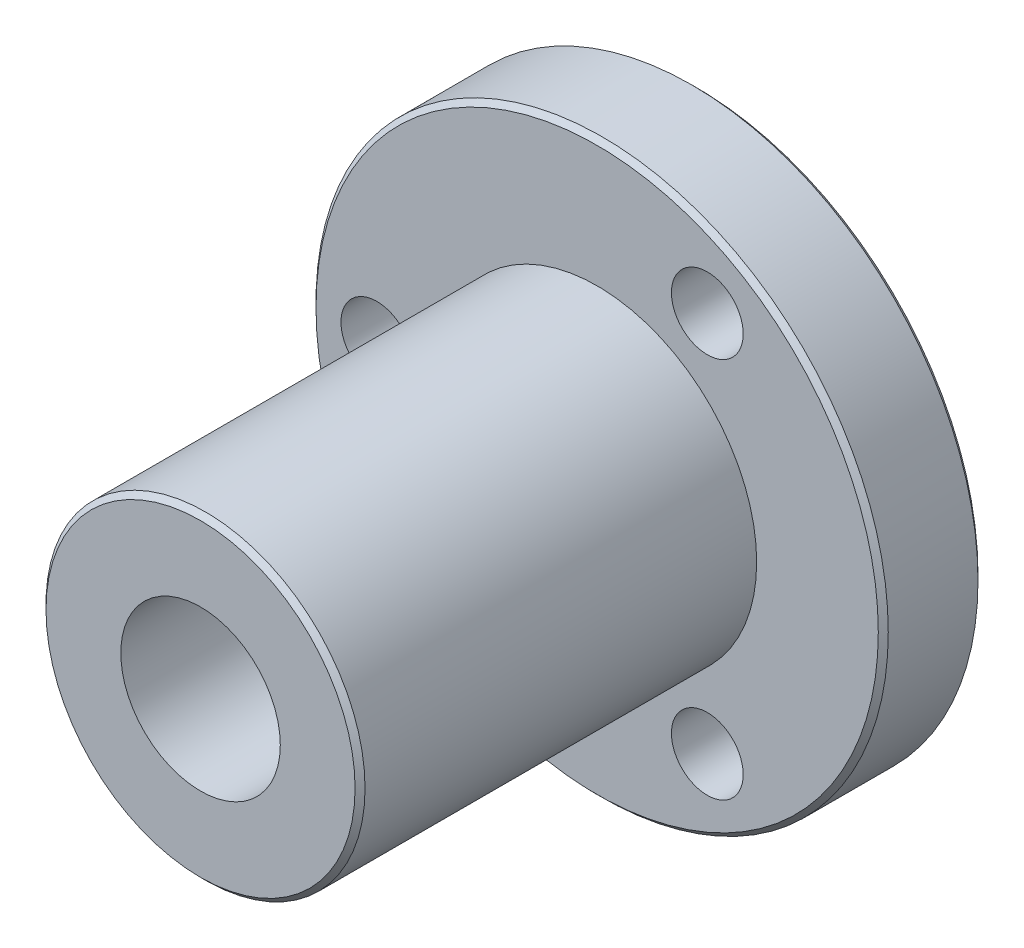
SolidWorks part; units mm, degrees
ref_plane "Front Plane" through (0, 0, 0) normal (0, 0, 1) x (1, 0, 0)
ref_plane "Top Plane" through (0, 0, 0) normal (0, 1, 0) x (1, 0, 0)
ref_plane "Right Plane" through (0, 0, 0) normal (1, 0, 0) x (0, 0, -1)
sketch "Sketch1" plane through (0, 0, 0) normal (0, 1, 0) x (1, 0, 0)
  line L0 (14.351, 0) -> (0, 0)
  line L1 (0, 0) -> (0, -5)
  line L2 (0, -5) -> (14.351, -5)
  line L3 (14.351, -5) -> (14.351, 0)
  line L4 (0, 0) -> (0, -5) construction
revolve "Revolve1" add sketch "Sketch1" angle 360 about L4
sketch "Sketch2" plane through (0, 0, 5) normal (0, 0, 1) x (1, 0, 0)
  circle A0 centre (0, 0) radius 8.001
extrude "Boss-Extrude1" add sketch "Sketch2" along normal blind 19.892
hole_wizard "Ø3.6 (3.6) Diameter Hole1" positions "Sketch4" profile "Sketch3" hole size "Ø3.6" standard "ANSI Metric"
sketch "Sketch4" plane through (0, 0, 5) normal (0, 0, 1) x (1, 0, 0)
  point P0 (5.5245, -9.5687)
  point P1 (-11.049, 0)
  point P2 (5.5245, 9.5687)
sketch "Sketch3" plane through (5.5245, -9.5687, 5) normal (1, 0, 0) x (0, -1, 0)
  line L0 (0, 0) -> (0, 5)
  line L1 (0, 5) -> (1.8, 5)
  line L2 (1.8, 5) -> (1.8, 0)
  line L5 (1.8, 0) -> (0, 0)
  line L11 (0, -6.35) -> (0, 107.95) construction
  dimension "Thru Hole Dia." = 3.6
  dimension "Thru Hole Depth" = 5
hole_wizard "Ø8.0 (8) Diameter Hole1" positions "Sketch6" profile "Sketch5" hole size "Ø8.0" standard "ANSI Metric"
sketch "Sketch6" plane through (0, 0, 24.892) normal (0, 0, 1) x (1, 0, 0)
  point P0 (0, 0)
sketch "Sketch5" plane through (0, 0, 24.892) normal (1, 0, 0) x (0, -1, 0)
  line L0 (0, 0) -> (0, 24.892)
  line L1 (0, 24.892) -> (4, 24.892)
  line L2 (4, 24.892) -> (4, 0)
  line L5 (4, 0) -> (0, 0)
  line L11 (0, -6.35) -> (0, 107.95) construction
  dimension "Thru Hole Dia." = 8
  dimension "Thru Hole Depth" = 24.892
chamfer "Chamfer1" distance 0.25 angle 45 3 edges at (14.351, 0, 0) (8.001, 0, 24.892) (14.351, 0, 5)
